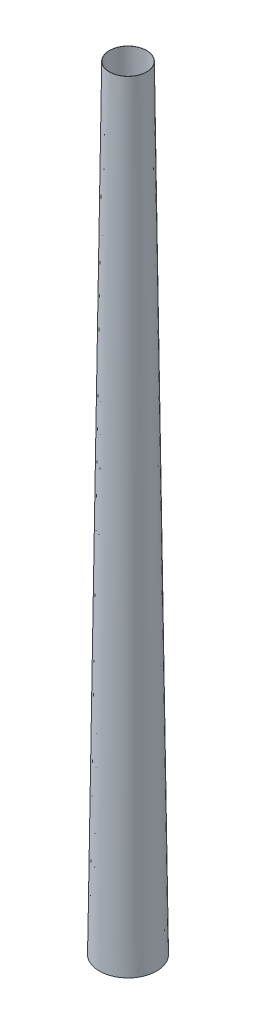
SolidWorks part; units mm, degrees
ref_plane "Front Plane" through (0, 0, 0) normal (0, 0, 1) x (1, 0, 0)
ref_plane "Top Plane" through (0, 0, 0) normal (0, 1, 0) x (1, 0, 0)
ref_plane "Right Plane" through (0, 0, 0) normal (1, 0, 0) x (0, 0, -1)
sketch "Sketch1" plane through (0, 0, 0) normal (0, 0, 1) x (1, 0, 0)
  line L0 (0, 0) -> (4959, 0) construction
  line L1 (4959, 0) -> (5000, 0)
  line L2 (0, 0) -> (0, 135000) construction
  line L3 (0, 135000) -> (3230, 135000) construction
  line L4 (3230, 135000) -> (3254, 135000)
  line L5 (3230, 135000) -> (4959, 0)
  line L6 (5000, 0) -> (3254, 135000)
  dimension "D1" = 4959
  dimension "D2" = 41
  dimension "D3" = 3230
  dimension "D4" = 24
revolve "Revolve1" add sketch "Sketch1" angle 360 about L2
